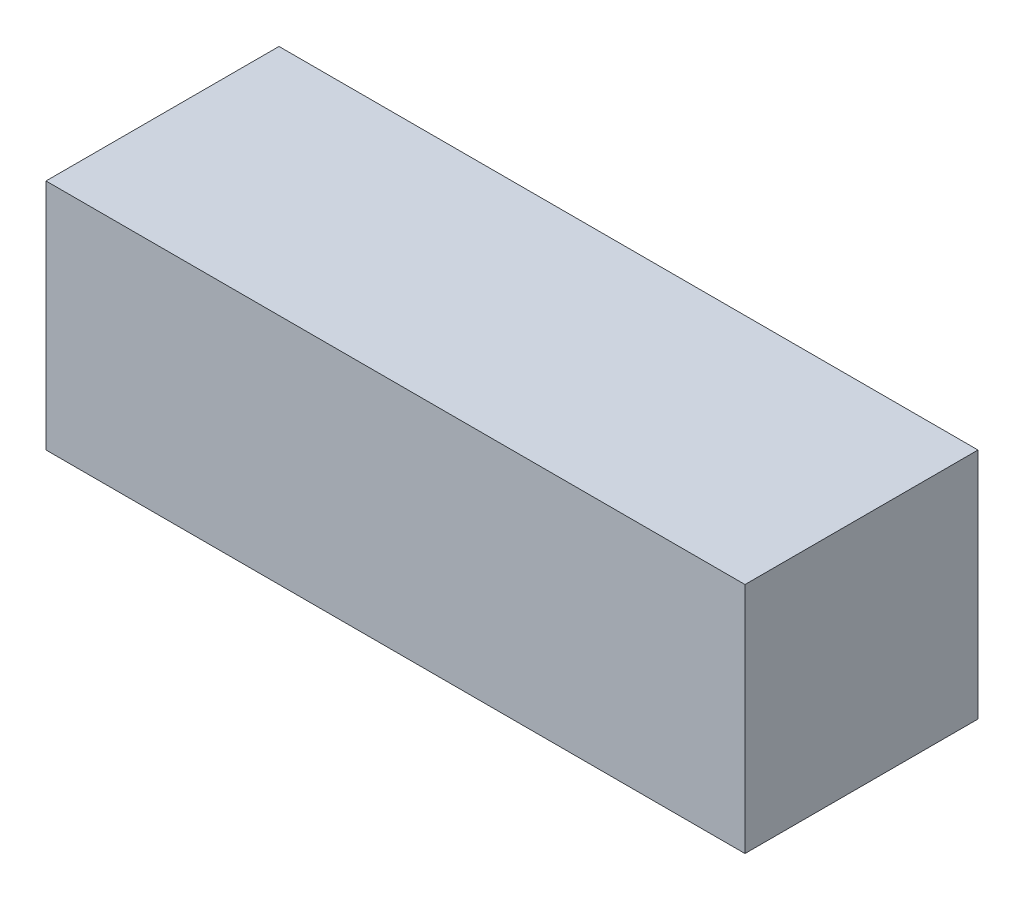
SolidWorks part; units mm, degrees
ref_plane "前视基准面" through (0, 0, 0) normal (0, 0, 1) x (1, 0, 0)
ref_plane "上视基准面" through (0, 0, 0) normal (0, 1, 0) x (1, 0, 0)
ref_plane "右视基准面" through (0, 0, 0) normal (1, 0, 0) x (0, 0, -1)
sketch "草图1" plane through (0, 0, 0) normal (0, 0, 1) x (1, 0, 0)
  line L1 (60, -20) -> (-60, -20)
  line L2 (60, -20) -> (60, 20)
  line L3 (60, 20) -> (-60, 20)
  line L4 (-60, -20) -> (-60, 20)
  line L5 (60, -20) -> (-60, 20) construction
  line L6 (60, 20) -> (-60, -20) construction
  point P0 (0, 0)
  dimension "D1" = 120
  dimension "D2" = 40
extrude "凸台-拉伸1" add sketch "草图1" along normal blind 40
